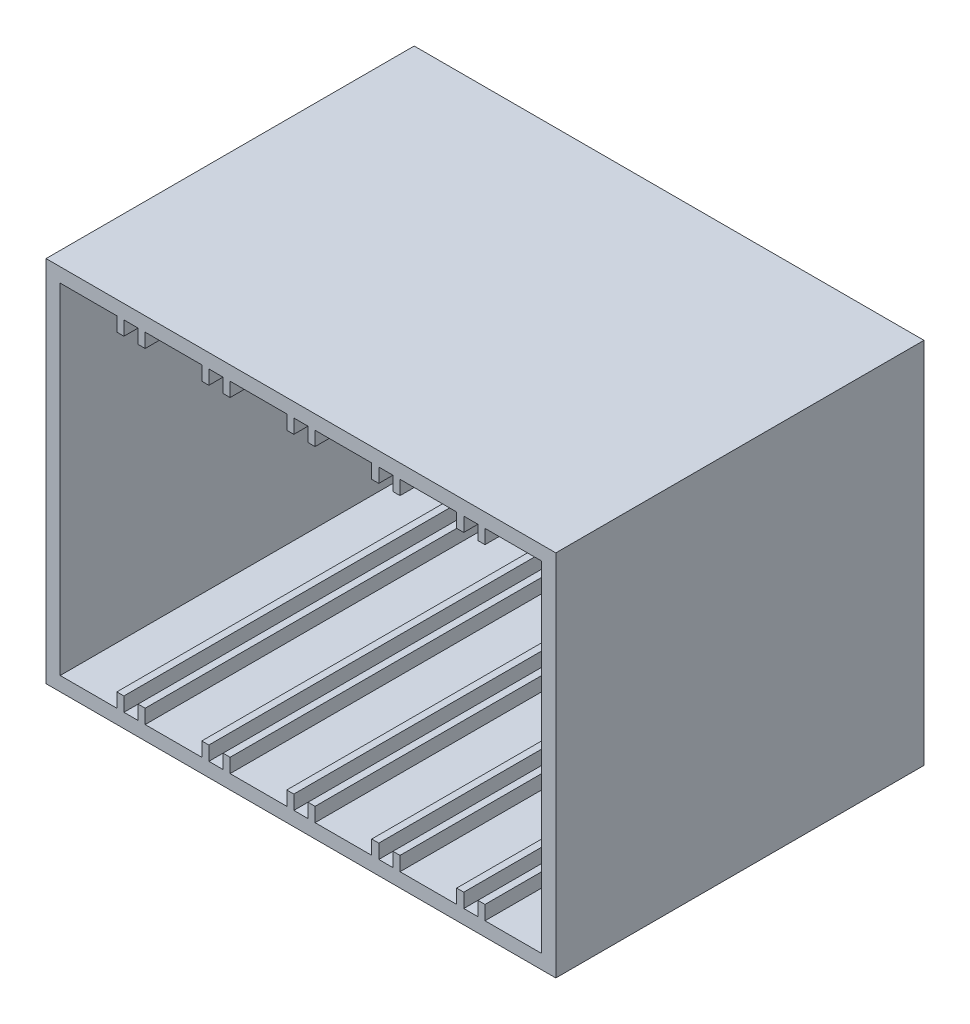
SolidWorks part; units mm, degrees
material "ABS"
ref_plane "Front Plane" through (0, 0, 0) normal (0, 0, 1) x (1, 0, 0)
ref_plane "Top Plane" through (0, 0, 0) normal (0, 1, 0) x (1, 0, 0)
ref_plane "Right Plane" through (0, 0, 0) normal (1, 0, 0) x (0, 0, -1)
sketch "Sketch2" plane through (0, 0, 0) normal (0, 0, 1) x (1, 0, 0)
  line L0 (-44.45, -3.175) -> (-44.45, 9.525)
  line L1 (-114.3, 3.175) -> (114.3, 3.175)
  line L2 (-114.3, 3.175) -> (-114.3, -3.175)
  line L3 (-114.3, -3.175) -> (114.3, -3.175)
  line L4 (114.3, 3.175) -> (114.3, -3.175)
  line L5 (-114.3, 3.175) -> (114.3, -3.175) construction
  line L6 (-114.3, -3.175) -> (114.3, 3.175) construction
  line L7 (-82.55, -3.175) -> (-79.375, -3.175)
  line L8 (-82.55, -3.175) -> (-82.55, 9.525)
  line L9 (-82.55, 9.525) -> (-79.375, 9.525)
  line L10 (-79.375, -3.175) -> (-79.375, 9.525)
  line L11 (-73.025, -3.175) -> (-69.85, -3.175)
  line L12 (-73.025, -3.175) -> (-73.025, 9.525)
  line L13 (-73.025, 9.525) -> (-69.85, 9.525)
  line L14 (-69.85, -3.175) -> (-69.85, 9.525)
  line L15 (-44.45, 9.525) -> (-41.275, 9.525)
  line L16 (-41.275, -3.175) -> (-41.275, 9.525)
  line L17 (-34.925, -3.175) -> (-34.925, 9.525)
  line L18 (-31.75, -3.175) -> (-31.75, 9.525)
  line L19 (-34.925, 9.525) -> (-31.75, 9.525)
  line L20 (-6.35, -3.175) -> (-6.35, 9.525)
  line L21 (-6.35, 9.525) -> (-3.175, 9.525)
  line L22 (-3.175, -3.175) -> (-3.175, 9.525)
  line L23 (3.175, -3.175) -> (3.175, 9.525)
  line L24 (6.35, -3.175) -> (6.35, 9.525)
  line L25 (3.175, 9.525) -> (6.35, 9.525)
  line L26 (31.75, -3.175) -> (31.75, 9.525)
  line L27 (31.75, 9.525) -> (34.925, 9.525)
  line L28 (34.925, -3.175) -> (34.925, 9.525)
  line L29 (41.275, -3.175) -> (41.275, 9.525)
  line L30 (44.45, -3.175) -> (44.45, 9.525)
  line L31 (41.275, 9.525) -> (44.45, 9.525)
  line L32 (69.85, -3.175) -> (69.85, 9.525)
  line L33 (69.85, 9.525) -> (73.025, 9.525)
  line L34 (73.025, -3.175) -> (73.025, 9.525)
  line L35 (79.375, -3.175) -> (79.375, 9.525)
  line L36 (82.55, -3.175) -> (82.55, 9.525)
  line L37 (79.375, 9.525) -> (82.55, 9.525)
  line L38 (-82.55, -3.175) -> (-44.45, -3.175) construction
  line L39 (-114.3, 79.375) -> (114.3, 79.375) construction
  line L40 (-114.3, -3.175) -> (-107.95, -3.175)
  line L41 (-114.3, -3.175) -> (-114.3, 161.925)
  line L42 (-114.3, 161.925) -> (-107.95, 161.925)
  line L43 (-107.95, -3.175) -> (-107.95, 161.925)
  line L44 (-114.3, 161.925) -> (114.3, 161.925)
  line L45 (-114.3, 161.925) -> (-114.3, 155.575)
  line L46 (-114.3, 155.575) -> (114.3, 155.575)
  line L47 (114.3, 161.925) -> (114.3, 155.575)
  line L48 (114.3, -3.175) -> (107.95, -3.175)
  line L49 (114.3, -3.175) -> (114.3, 161.925)
  line L50 (114.3, 161.925) -> (107.95, 161.925)
  line L51 (107.95, -3.175) -> (107.95, 161.925)
  line L52 (82.55, 161.925) -> (82.55, 149.225)
  line L53 (79.375, 149.225) -> (82.55, 149.225)
  line L54 (79.375, 161.925) -> (79.375, 149.225)
  line L55 (73.025, 161.925) -> (73.025, 149.225)
  line L56 (69.85, 149.225) -> (73.025, 149.225)
  line L57 (69.85, 161.925) -> (69.85, 149.225)
  line L58 (44.45, 161.925) -> (44.45, 149.225)
  line L59 (41.275, 149.225) -> (44.45, 149.225)
  line L60 (41.275, 161.925) -> (41.275, 149.225)
  line L61 (31.75, 161.925) -> (31.75, 149.225)
  line L62 (31.75, 149.225) -> (34.925, 149.225)
  line L63 (34.925, 161.925) -> (34.925, 149.225)
  line L64 (6.35, 161.925) -> (6.35, 149.225)
  line L65 (3.175, 149.225) -> (6.35, 149.225)
  line L66 (3.175, 161.925) -> (3.175, 149.225)
  line L67 (-3.175, 161.925) -> (-3.175, 149.225)
  line L68 (-6.35, 149.225) -> (-3.175, 149.225)
  line L69 (-6.35, 161.925) -> (-6.35, 149.225)
  line L70 (-31.75, 161.925) -> (-31.75, 149.225)
  line L71 (-34.925, 149.225) -> (-31.75, 149.225)
  line L72 (-34.925, 161.925) -> (-34.925, 149.225)
  line L73 (-41.275, 161.925) -> (-41.275, 149.225)
  line L74 (-44.45, 149.225) -> (-41.275, 149.225)
  line L75 (-44.45, 161.925) -> (-44.45, 149.225)
  line L76 (-69.85, 161.925) -> (-69.85, 149.225)
  line L77 (-73.025, 149.225) -> (-69.85, 149.225)
  line L78 (-73.025, 161.925) -> (-73.025, 149.225)
  line L79 (-79.375, 161.925) -> (-79.375, 149.225)
  line L80 (-82.55, 149.225) -> (-79.375, 149.225)
  line L81 (-82.55, 161.925) -> (-82.55, 149.225)
  point P0 (0, 0)
  point P14 (-114.3, 0)
  dimension "D1" = 228.6
  dimension "D2" = 6.35
  dimension "D3" = 12.7
  dimension "D4" = 3.175
  dimension "D5" = 6.35
  dimension "D6" = 31.75
  dimension "D8" = 38.1
  dimension "D9" = 165.1
  dimension "D10" = 6.35
  dimension "D11" = 6.35
  dimension "D12" = 6.35
  dimension "D7" = 5
extrude "Boss-Extrude1" add sketch "Sketch2" along normal blind 152.4 contours L46 L41 L1 L43 | L41 L46 L43 L42 | L81 L44 L43 L46 | L44 L81 L46 L79 | L44 L79 L46 L78 | L44 L78 L46 L76 | L44 L76 L46 L75 | L44 L75 L46 L73 | L46 L75 L74 L73 | L44 L73 L46 L72 | L44 L72 L46 L70 | L46 L72 L71 L70 | L44 L70 L46 L69 | L44 L69 L46 L67 | L46 L69 L68 L67 | L44 L67 L46 L66 | L44 L66 L46 L64 | L46 L66 L65 L64 | L44 L64 L46 L61 | L63 L44 L61 L46 | L44 L63 L46 L60 | L63 L46 L61 L62 | L46 L60 L59 L58 | L44 L60 L46 L58 | L44 L58 L46 L57 | L44 L57 L46 L55 | L46 L57 L56 L55 | L44 L55 L46 L54 | L44 L54 L46 L52 | L46 L54 L53 L52 | L44 L52 L46 L51 | L51 L46 L47 L44 | L51 L1 L49 L46 | L3 L43 L1 L2 | L43 L3 L8 L1 | L3 L10 L1 L8 | L1 L10 L9 L8 | L3 L12 L1 L10 | L3 L14 L1 L12 | L1 L14 L13 L12 | L14 L3 L0 L1 | L3 L16 L1 L0 | L1 L16 L15 L0 | L3 L17 L1 L16 | L3 L18 L1 L17 | L19 L17 L1 L18 | L3 L20 L1 L18 | L3 L22 L1 L20 | L1 L22 L21 L20 | L3 L23 L1 L22 | L3 L24 L1 L23 | L25 L23 L1 L24 | L3 L26 L1 L24 | L51 L3 L4 L1 | L3 L51 L1 L36 | L3 L36 L1 L35 | L37 L35 L1 L36 | L1 L34 L33 L32 | L3 L35 L1 L34 | L3 L34 L1 L32 | L3 L32 L1 L30 | L31 L29 L1 L30 | L1 L28 L27 L26 | L3 L28 L1 L26 | L3 L29 L1 L28 | L3 L30 L1 L29 | L46 L81 L80 L79 | L46 L78 L77 L76
sketch "Sketch3" plane through (0, 0, 0) normal (0, 0, -1) x (-1, 0, 0)
  line L4 (114.3, 161.925) -> (-114.3, 161.925)
  line L5 (-114.3, 161.925) -> (-114.3, -3.175)
  line L6 (-114.3, -3.175) -> (114.3, -3.175)
  line L7 (114.3, -3.175) -> (114.3, 161.925)
  line L8 (114.3, 161.925) -> (-114.3, 161.925)
  line L9 (-114.3, 161.925) -> (-114.3, -3.175)
  line L10 (-114.3, -3.175) -> (114.3, -3.175)
  line L11 (114.3, -3.175) -> (114.3, 161.925)
  dimension "D1" = 0
extrude "Boss-Extrude2" add sketch "Sketch3" along normal blind 12.7
